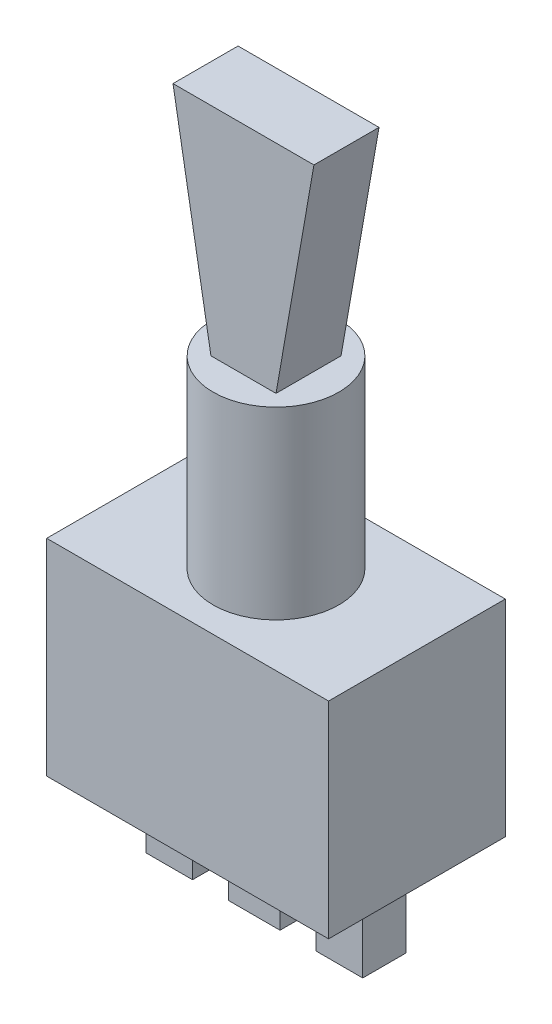
SolidWorks part; units mm, degrees
ref_plane "Front Plane" through (0, 0, 0) normal (0, 0, 1) x (1, 0, 0)
ref_plane "Top Plane" through (0, 0, 0) normal (0, 1, 0) x (1, 0, 0)
ref_plane "Right Plane" through (0, 0, 0) normal (1, 0, 0) x (0, 0, -1)
sketch "Sketch1" plane through (0, 0, 0) normal (0, 1, 0) x (1, 0, 0)
  line L1 (-6.5, -4.075) -> (6.5, -4.075)
  line L2 (-6.5, -4.075) -> (-6.5, 4.075)
  line L3 (-6.5, 4.075) -> (6.5, 4.075)
  line L4 (6.5, -4.075) -> (6.5, 4.075)
  line L5 (-6.5, -4.075) -> (6.5, 4.075) construction
  line L6 (-6.5, 4.075) -> (6.5, -4.075) construction
  point P0 (0, 0)
  dimension "D1" = 13
  dimension "D2" = 8.15
extrude "Boss-Extrude1" add sketch "Sketch1" against normal blind 9.5
sketch "Sketch2" plane through (0, 0, 0) normal (0, 1, 0) x (1, 0, 0)
  circle A0 centre (0, 0) radius 2.9
  dimension "D1" = 5.8
extrude "Boss-Extrude2" add sketch "Sketch2" along normal blind 8.5
sketch "Sketch3" plane through (0, 0, 0) normal (0, 0, 1) x (1, 0, 0)
  line L0 (0, 8.5) -> (0, 18.5) construction
  line L1 (2.9, 8.5) -> (-2.9, 8.5) construction
  line L2 (3.25, 18.5) -> (-3.25, 18.5)
  line L3 (1.5, 8.5) -> (-1.5, 8.5)
  line L4 (-1.5, 8.5) -> (-3.25, 18.5)
  line L5 (1.5, 8.5) -> (3.25, 18.5)
  dimension "D1" = 10
  dimension "D2" = 3.25
  dimension "D3" = 1.5
extrude "Boss-Extrude3" add sketch "Sketch3" along normal blind 1.5 and the other way blind 1.5
sketch "Sketch4" plane through (0, -9.5, 0) normal (0, -1, 0) x (1, 0, 0)
  line L1 (-5, -1) -> (5, -1)
  line L2 (-5, -1) -> (-5, 1)
  line L3 (-5, 1) -> (5, 1)
  line L4 (5, -1) -> (5, 1)
  line L5 (-5, -1) -> (5, 1) construction
  line L6 (-5, 1) -> (5, -1) construction
  point P0 (0, 0)
  dimension "D1" = 2
  dimension "D2" = 10
extrude "Boss-Extrude4" add sketch "Sketch4" along normal blind 3.85
sketch "Sketch5" plane through (0, 0, 0) normal (0, 0, 1) x (1, 0, 0)
  line L0 (5, -13.35) -> (-5, -13.35) construction
  line L1 (-2.8487, -13.35) -> (-1.1859, -13.35)
  line L2 (-2.8487, -13.35) -> (-2.8487, -9.5)
  line L3 (-2.8487, -9.5) -> (-1.1859, -9.5)
  line L4 (-1.1859, -13.35) -> (-1.1859, -9.5)
  line L5 (5, -9.5) -> (-5, -9.5) construction
  line L6 (0, -13.35) -> (0, -9.5) construction
  line L7 (-6.5, -9.5) -> (6.5, -9.5) construction
  line L8 (1.1859, -13.35) -> (1.1859, -9.5)
  line L9 (2.8487, -9.5) -> (1.1859, -9.5)
  line L10 (2.8487, -13.35) -> (2.8487, -9.5)
  line L11 (2.8487, -13.35) -> (1.1859, -13.35)
extrude "Cut-Extrude1" cut sketch "Sketch5" against normal through all both and the other way through all
